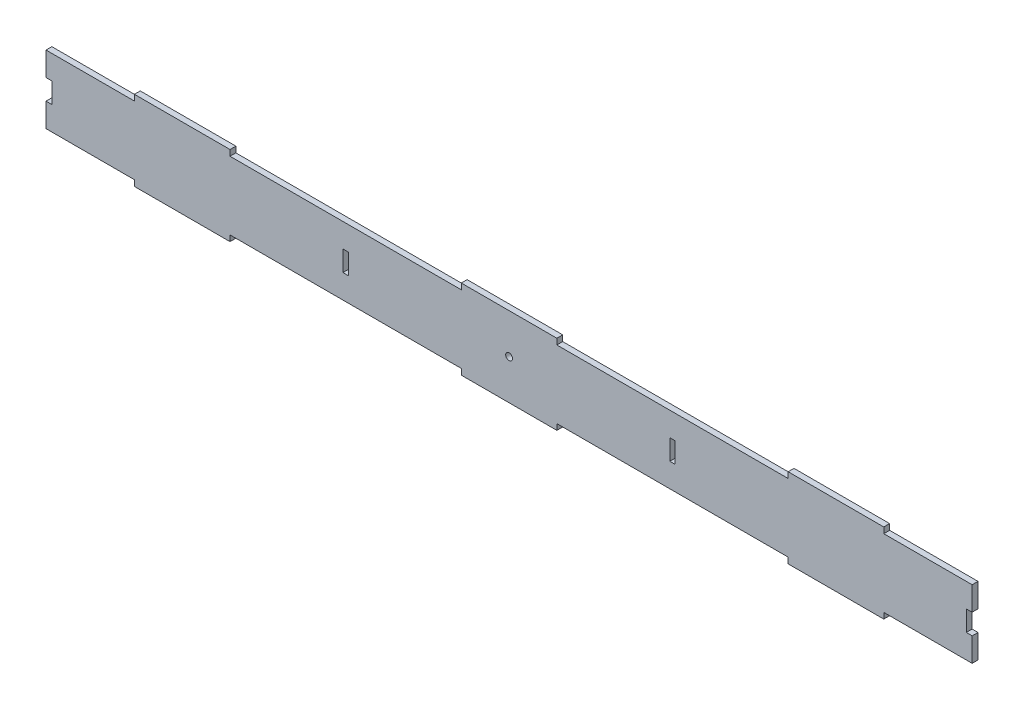
SolidWorks part; units mm, degrees
ref_plane "Front Plane" through (0, 0, 0) normal (0, 0, 1) x (1, 0, 0)
ref_plane "Top Plane" through (0, 0, 0) normal (0, 1, 0) x (1, 0, 0)
ref_plane "Right Plane" through (0, 0, 0) normal (1, 0, 0) x (0, 0, -1)
sketch "Sketch1" plane through (0, 0, 0) normal (0, 0, 1) x (1, 0, 0)
  line L0 (-335.7, 0) -> (335.7, 0) construction
  line L1 (-340, -25) -> (-275.1, -25)
  line L2 (-340, -25) -> (-340, -7.5)
  line L3 (-340, 25) -> (-275.1, 25)
  line L4 (340, -25) -> (340, -7.5)
  line L5 (-340, -25) -> (340, 25) construction
  line L6 (-340, 25) -> (340, -25) construction
  line L7 (0, -25) -> (0, 25) construction
  line L8 (35.1, -25) -> (204.9, -25)
  line L10 (-275.1, -25) -> (-275.1, -29.3)
  line L11 (-275.1, -29.3) -> (-204.9, -29.3)
  line L12 (-204.9, -25) -> (-204.9, -29.3)
  line L14 (-35.1, -25) -> (-35.1, -29.3)
  line L15 (-35.1, -29.3) -> (35.1, -29.3)
  line L16 (35.1, -25) -> (35.1, -29.3)
  line L18 (204.9, -25) -> (204.9, -29.3)
  line L19 (204.9, -29.3) -> (275.1, -29.3)
  line L20 (275.1, -25) -> (275.1, -29.3)
  line L21 (275.1, -25) -> (340, -25)
  line L22 (-204.9, -25) -> (-35.1, -25)
  line L23 (275.1, 25) -> (275.1, 29.3)
  line L24 (204.9, 29.3) -> (275.1, 29.3)
  line L25 (204.9, 25) -> (204.9, 29.3)
  line L26 (35.1, 25) -> (35.1, 29.3)
  line L27 (-35.1, 29.3) -> (35.1, 29.3)
  line L28 (-35.1, 25) -> (-35.1, 29.3)
  line L29 (-204.9, 25) -> (-204.9, 29.3)
  line L30 (-275.1, 29.3) -> (-204.9, 29.3)
  line L31 (-275.1, 25) -> (-275.1, 29.3)
  line L32 (-204.9, 25) -> (-35.1, 25)
  line L33 (35.1, 25) -> (204.9, 25)
  line L34 (275.1, 25) -> (340, 25)
  line L35 (-340, 7.5) -> (-340, 25)
  line L36 (-340, 7.5) -> (-335.7, 7.5)
  line L38 (-340, -7.5) -> (-335.7, -7.5)
  line L39 (-335.7, 7.5) -> (-335.7, -7.5)
  line L40 (335.7, 7.5) -> (335.7, -7.5)
  line L41 (340, -7.5) -> (335.7, -7.5)
  line L42 (340, 7.5) -> (335.7, 7.5)
  line L43 (340, 7.5) -> (340, 25)
  line L44 (122, 7.5) -> (118, 7.5)
  line L45 (-122, -7.5) -> (-118, -7.5)
  line L46 (-122, -7.5) -> (-122, 7.5)
  line L47 (-122, 7.5) -> (-118, 7.5)
  line L48 (-118, -7.5) -> (-118, 7.5)
  line L49 (-122, -7.5) -> (-118, 7.5) construction
  line L50 (-122, 7.5) -> (-118, -7.5) construction
  line L51 (118, -7.5) -> (118, 7.5)
  line L52 (122, -7.5) -> (118, -7.5)
  line L53 (122, -7.5) -> (122, 7.5)
  circle A0 centre (0, 0) radius 2.5
  point P0 (0, 0)
  point P22 (0, -29.3)
  point P23 (-335.7, 0)
  point P24 (240, -29.3)
  point P25 (-240, -29.3)
  point P38 (-120, 0)
  point P52 (-120, 25)
  dimension "D11" = 5
  dimension "D1" = 50
  dimension "D2" = 680
  dimension "D3" = 4.3
  dimension "D4" = 70.2
  dimension "D5" = 240
  dimension "D6" = 240
  dimension "D7" = 15
  dimension "D8" = 4
  dimension "D9" = 15
  dimension "D10" = 4.3
extrude "Boss-Extrude1" add sketch "Sketch1" along normal blind 4.3
